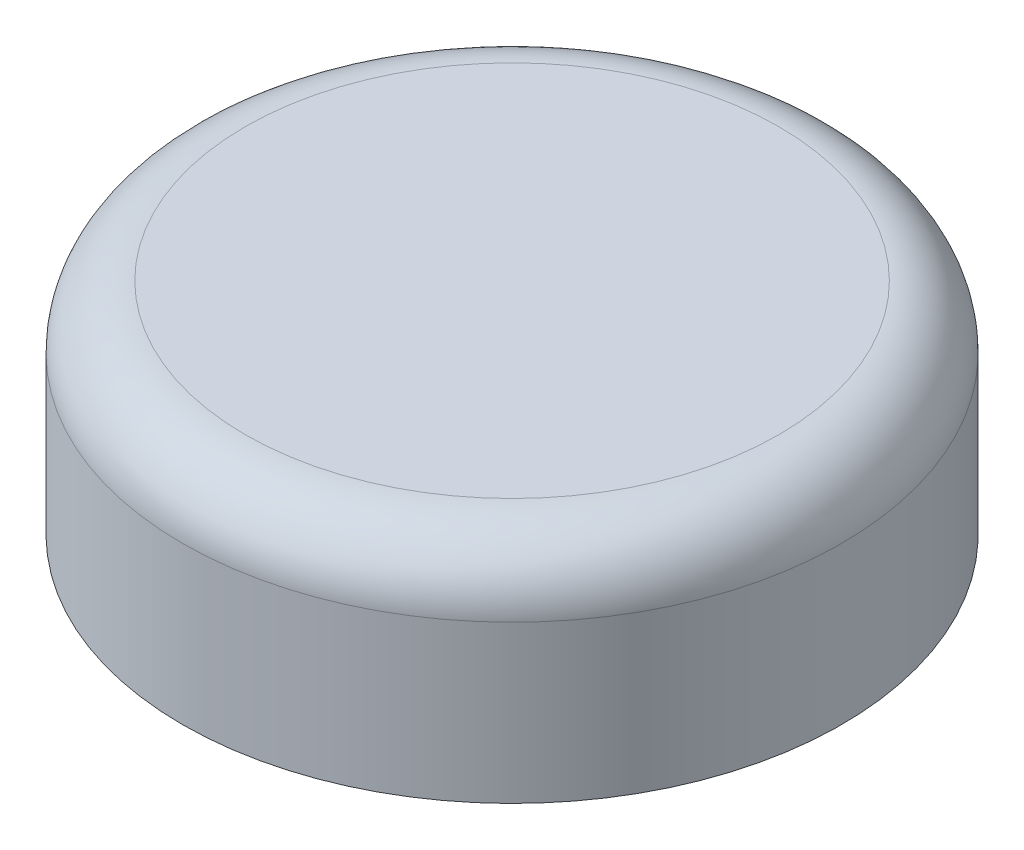
SolidWorks part; units mm, degrees
material "ABS"
ref_plane "Front Plane" through (0, 0, 0) normal (0, 0, 1) x (1, 0, 0)
ref_plane "Top Plane" through (0, 0, 0) normal (0, 1, 0) x (1, 0, 0)
ref_plane "Right Plane" through (0, 0, 0) normal (1, 0, 0) x (0, 0, -1)
sketch "Sketch1" plane through (0, 0, 0) normal (0, 1, 0) x (1, 0, 0)
  circle A0 centre (0, 0) radius 10.5
extrude "Boss-Extrude2" add sketch "Sketch1" along normal blind 7
fillet "Fillet1" radius 2 1 edges at (0, 7, 10.5)
